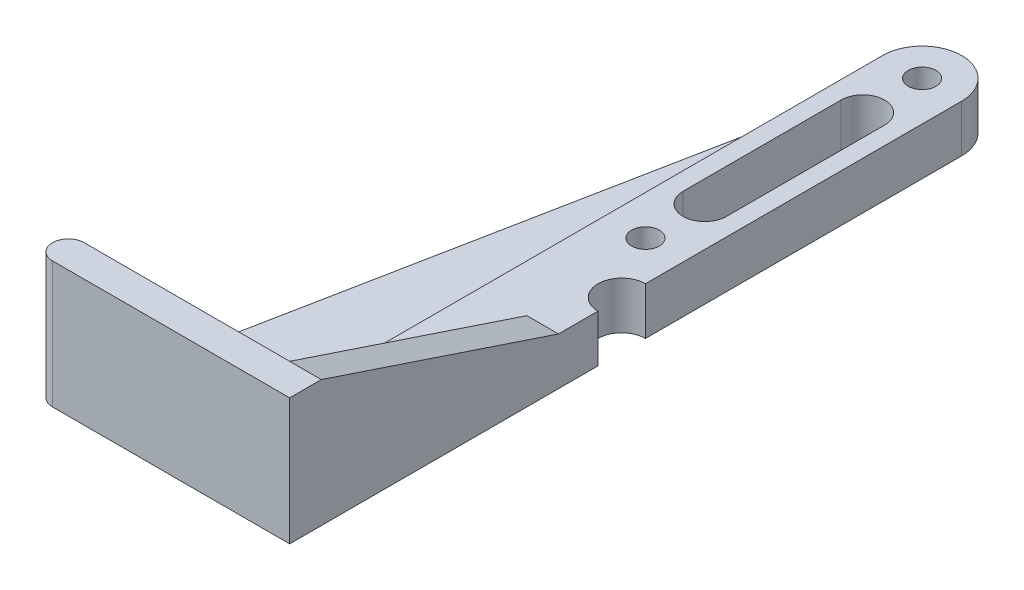
SolidWorks part; units mm, degrees
ref_plane "Front Plane" through (0, 0, 0) normal (0, 0, 1) x (1, 0, 0)
ref_plane "Top Plane" through (0, 0, 0) normal (0, 1, 0) x (1, 0, 0)
ref_plane "Right Plane" through (0, 0, 0) normal (1, 0, 0) x (0, 0, -1)
sketch "Sketch1" plane through (0, 0, 0) normal (0, 1, 0) x (1, 0, 0)
  line L1 (5, 0) -> (5, -85)
  line L2 (-5, 0) -> (-5, -85)
  line L9 (-5, -85) -> (5, -85)
  arc A0 (5, 0) -> (-5, 0) centre (0, 0) ccw
  dimension "D1" = 85
  dimension "D2" = 10
extrude "Boss-Extrude1" add sketch "Sketch1" along normal blind 6
sketch "Sketch2" plane through (0, 6, 0) normal (0, 1, 0) x (1, 0, 0)
  line L1 (5, -81) -> (5, -85)
  line L2 (5, -85) -> (-25, -85)
  line L4 (-25, -81) -> (5, -81)
  arc A2 (-25, -81) -> (-25, -85) centre (-25, -83) ccw
  dimension "D1" = 30
  dimension "D3" = 4
extrude "Boss-Extrude2" add sketch "Sketch2" along normal blind 10 and the other way up to surface other way up to face at (0, 0, 41.25)
sketch "Sketch3" plane through (0, 0, 0) normal (0, 1, 0) x (1, 0, 0)
  line L0 (-5, 0.4862) -> (-21, -81)
  line L2 (5, -81) -> (-25, -81) construction
  line L4 (-5, 0) -> (-5, -81) construction
  arc A1 (5, 0) -> (-5, 0) centre (0, 0) ccw construction
  point P2 (-5, 6.1137)
  dimension "D2" = 16
rib "Rib1" sketch "Sketch3" sketch "Sketch3" thickness 3 parameters "D1"=3
sketch "Sketch4" plane through (0, 6, 0) normal (0, 1, 0) x (1, 0, 0)
  line L0 (0, -7.5) -> (0, -27.5) construction
  line L1 (2.75, -7.5) -> (2.75, -27.5)
  line L2 (-2.75, -7.5) -> (-2.75, -27.5)
  arc A0 (2.75, -7.5) -> (-2.75, -7.5) centre (0, -7.5) ccw
  arc A1 (-2.75, -27.5) -> (2.75, -27.5) centre (0, -27.5) ccw
  circle A2 centre (0, 0) radius 1.75
  circle A3 centre (0, -35) radius 1.75
  point P3 (0, -17.5)
  dimension "D4" = 3.5
  dimension "D1" = 20
  dimension "D2" = 5.5
  dimension "D3" = 7.5
  dimension "D5" = 35
extrude "Cut-Extrude1" cut sketch "Sketch4" against normal up to next
sketch "Sketch5" plane through (5, 0, 0) normal (1, 0, 0) x (0, 0, -1)
  line L0 (-81, 16) -> (-51, 6)
  line L1 (-81, 6) -> (0, 6) construction
  line L2 (-51, 6) -> (-81, 6)
  line L3 (-81, 6) -> (-81, 16)
  dimension "D1" = 30
extrude "Boss-Extrude3" add sketch "Sketch5" against normal blind 4
sketch "Sketch6" plane through (0, 6, 0) normal (0, 1, 0) x (1, 0, 0)
  line L0 (5, -51) -> (5, 0) construction
  line L1 (5, -40) -> (5, -46)
  arc A0 (5, -40) -> (5, -46) centre (5, -43) ccw
  point P3 (5, -40.4382)
  point P7 (0, 0)
  dimension "D2" = 3
  dimension "D1" = 43
extrude "Cut-Extrude2" cut sketch "Sketch6" against normal up to next
